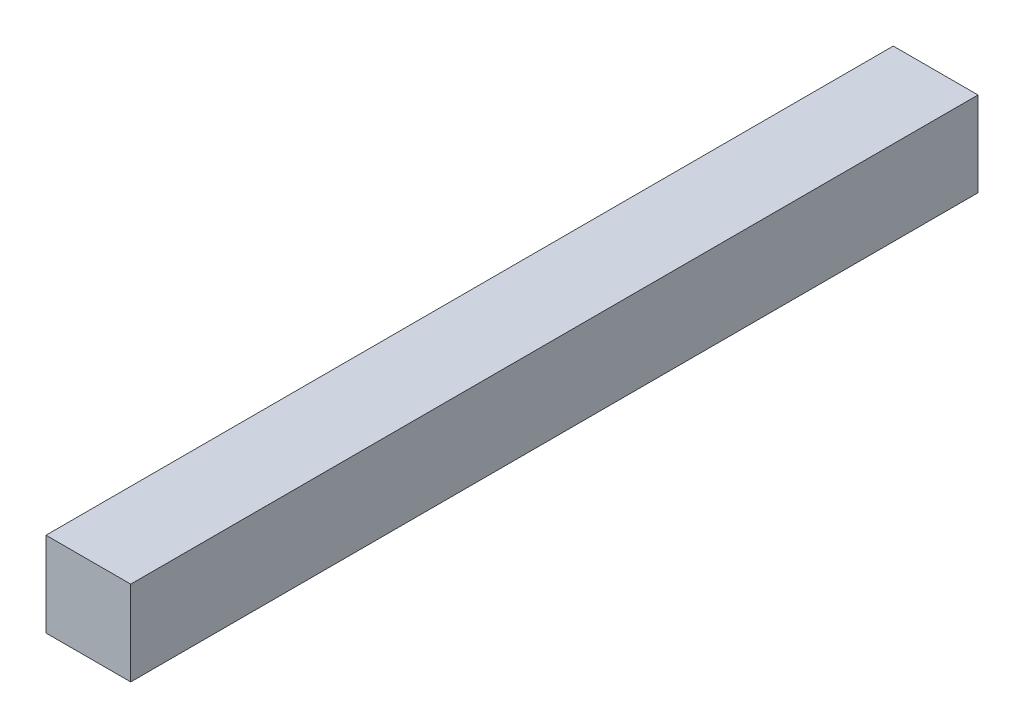
SolidWorks part; units mm, degrees
ref_plane "Plan de face" through (0, 0, 0) normal (0, 0, 1) x (1, 0, 0)
ref_plane "Plan de dessus" through (0, 0, 0) normal (0, 1, 0) x (1, 0, 0)
ref_plane "Plan de droite" through (0, 0, 0) normal (1, 0, 0) x (0, 0, -1)
sketch "Esquisse1" plane through (0, 0, 0) normal (0, 0, 1) x (1, 0, 0)
  line L1 (0, 0) -> (10, 0)
  line L2 (0, 0) -> (0, 10)
  line L3 (0, 10) -> (10, 10)
  line L4 (10, 0) -> (10, 10)
  dimension "D1" = 10
  dimension "D2" = 10
extrude "Boss.-Extru.1" add sketch "Esquisse1" along normal blind 100
